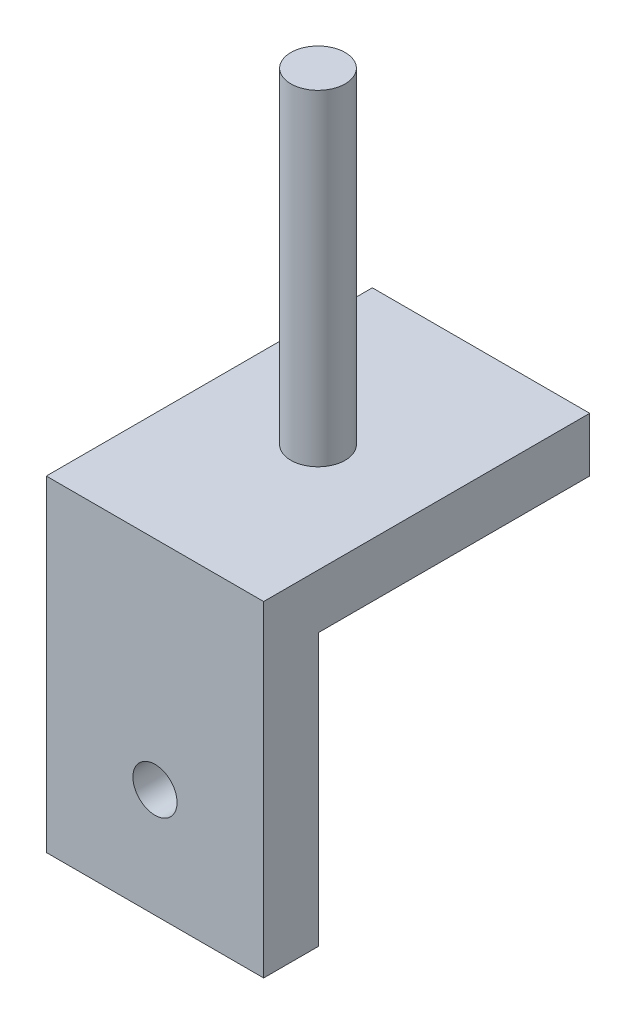
SolidWorks part; units mm, degrees
ref_plane "Front Plane" through (0, 0, 0) normal (0, 0, 1) x (1, 0, 0)
ref_plane "Top Plane" through (0, 0, 0) normal (0, 1, 0) x (1, 0, 0)
ref_plane "Right Plane" through (0, 0, 0) normal (1, 0, 0) x (0, 0, -1)
sketch "Sketch1" plane through (0, 0, 0) normal (0, 1, 0) x (1, 0, 0)
  line L1 (-25.4, 38.1) -> (25.4, 38.1)
  line L2 (-25.4, 38.1) -> (-25.4, -38.1)
  line L3 (-25.4, -38.1) -> (25.4, -38.1)
  line L4 (25.4, 38.1) -> (25.4, -38.1)
  line L5 (-25.4, 38.1) -> (25.4, -38.1) construction
  line L6 (-25.4, -38.1) -> (25.4, 38.1) construction
  point P0 (0, 0)
  dimension "D1" = 76.2
  dimension "D2" = 50.8
extrude "Boss-Extrude1" add sketch "Sketch1" along normal blind 12.7
sketch "Sketch2" plane through (0, 12.7, 0) normal (0, 1, 0) x (1, 0, 0)
  circle A0 centre (0, 0) radius 6.35
  dimension "D1" = 12.7
extrude "Boss-Extrude2" add sketch "Sketch2" along normal blind 76.2
sketch "Sketch4" plane through (0, 12.7, 0) normal (0, 1, 0) x (1, 0, 0)
  line L0 (25.4, -38.1) -> (25.4, 38.1) construction
  line L1 (-25.4, -38.1) -> (25.4, -38.1)
  line L2 (-25.4, -38.1) -> (-25.4, -25.292)
  line L3 (-25.4, -25.292) -> (25.4, -25.292)
  line L4 (25.4, -38.1) -> (25.4, -25.292)
  dimension "D1" = 12.808
extrude "Boss-Extrude3" add sketch "Sketch4" against normal blind 76.2
hole_wizard "13/32 (0.40625) Diameter Hole1" positions "Sketch5" profile "Sketch6" hole size "13/32" standard "ANSI Inch" end condition through all
sketch "Sketch5" plane through (0, 0, 25.292) normal (0, 0, -1) x (-1, 0, 0)
  line L0 (-25.4, -63.5) -> (25.4, -63.5) construction
  point P0 (0, -38.1)
  dimension "D1" = 25.4
sketch "Sketch6" plane through (0, -38.1, 25.292) normal (1, 0, 0) x (0, 1, 0)
  line L0 (0, 0) -> (0, 12.808)
  line L1 (0, 12.808) -> (5.1594, 12.808)
  line L2 (5.1594, 12.808) -> (5.1594, 0.635)
  line L3 (5.1594, 0.635) -> (5.7944, 0)
  line L5 (5.7944, 0) -> (0, 0)
  line L6 (-5.1594, 0.635) -> (-5.7944, 0) construction
  line L11 (0, -6.35) -> (0, 107.95) construction
  dimension "Thru Hole Dia." = 10.3187
  dimension "Thru Hole Depth" = 12.808
  dimension "Near C'Sink Dia." = 11.5887
  dimension "Near C'Sink Angle" = 90
